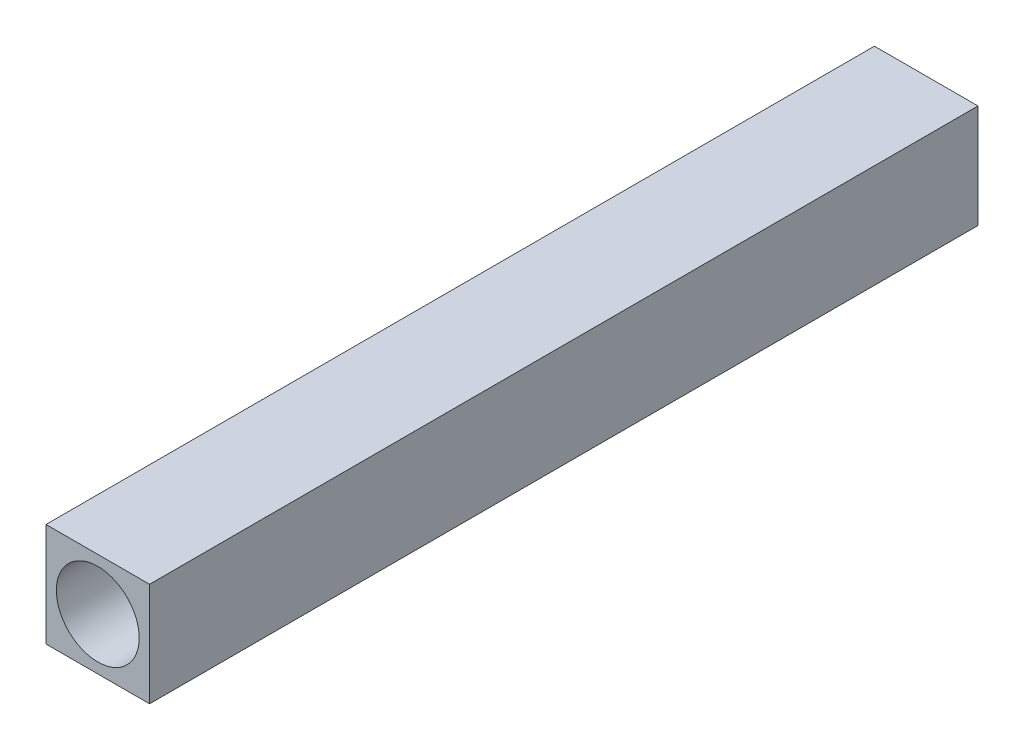
SolidWorks part; units mm, degrees
material "Custom Plastic"
ref_plane "Front Plane" through (0, 0, 0) normal (0, 0, 1) x (1, 0, 0)
ref_plane "Top Plane" through (0, 0, 0) normal (0, 1, 0) x (1, 0, 0)
ref_plane "Right Plane" through (0, 0, 0) normal (1, 0, 0) x (0, 0, -1)
other "Configuration Table"
sketch "Sketch1" plane through (0, 0, 0) normal (0, 0, 1) x (1, 0, 0)
  line L1 (-12.5, -12.5) -> (12.5, -12.5)
  line L2 (-12.5, -12.5) -> (-12.5, 12.5)
  line L3 (-12.5, 12.5) -> (12.5, 12.5)
  line L4 (12.5, -12.5) -> (12.5, 12.5)
  line L5 (-12.5, -12.5) -> (12.5, 12.5) construction
  line L6 (-12.5, 12.5) -> (12.5, -12.5) construction
  circle A0 centre (0, 0) radius 10
  dimension "D1" = 20
  dimension "D2" = 25
extrude "Boss-Extrude1" add sketch "Sketch1" along normal mid plane 200
